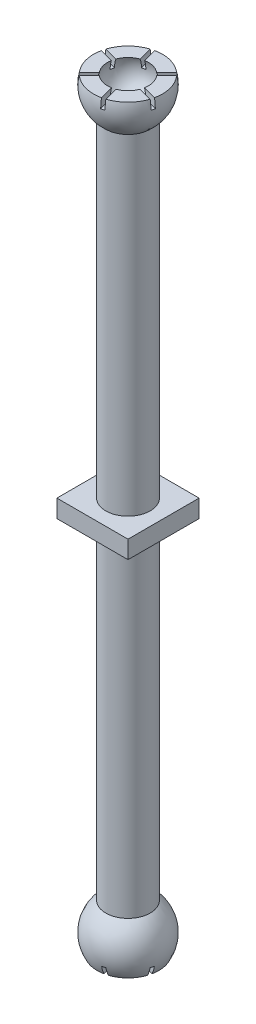
SolidWorks part; units mm, degrees
material "AISI 1020 Steel, Cold Rolled"
ref_plane "Front Plane" through (0, 0, 0) normal (0, 0, 1) x (1, 0, 0)
ref_plane "Top Plane" through (0, 0, 0) normal (0, 1, 0) x (1, 0, 0)
ref_plane "Right Plane" through (0, 0, 0) normal (1, 0, 0) x (0, 0, -1)
sketch "Sketch1" plane through (0, 0, 0) normal (0, 1, 0) x (1, 0, 0)
  circle A0 centre (0, 0) radius 25
  dimension "D1" = 50
extrude "Boss-Extrude1" add sketch "Sketch1" along normal blind 826
ref_plane "Plane1" through (0, 826, 0) normal (0, 1, 0) x (1, 0, 0)
sketch "Sketch2" plane through (0, 826, 0) normal (0, 1, 0) x (1, 0, 0)
  line L0 (0, 40) -> (0, -40)
  arc A0 (0, 40) -> (0, -40) centre (0, 0) ccw
  dimension "D1" = 40
revolve "Revolve1" add sketch "Sketch2" angle 360 about L0
ref_plane "Plane2" through (0, 836, 0) normal (0, 1, 0) x (1, 0, 0)
sketch "Sketch3" plane through (0, 0, 0) normal (0, -1, 0) x (1, 0, 0)
  line L0 (0, 40) -> (0, -40)
  arc A0 (0, 40) -> (0, -40) centre (0, 0) cw
  circle A1 centre (0, 0) radius 40 construction
sketch "Sketch4" plane through (0, 836, 0) normal (0, 1, 0) x (1, 0, 0)
  circle A0 centre (0, 0) radius 43.9337
extrude "Cut-Extrude1" cut sketch "Sketch4" along normal through all
ref_plane "Plane3" through (0, -10, 0) normal (0, -1, 0) x (-1, 0, 0)
revolve "Revolve3" add sketch "Sketch3" angle 360 about L0
ref_plane "Plane4" through (0, -20, 0) normal (0, -1, 0) x (-1, 0, 0)
sketch "Sketch6" plane through (0, -20, 0) normal (0, -1, 0) x (-1, 0, 0)
  circle A0 centre (0, 0) radius 44.2735
extrude "Cut-Extrude2" cut sketch "Sketch6" along normal through all
sketch "Sketch7" plane through (0, 826, 0) normal (0, 1, 0) x (1, 0, 0)
  line L0 (14.2673, 20.5291) -> (-14.2673, -20.5291)
  arc A0 (14.2673, 20.5291) -> (-14.2673, -20.5291) centre (0, 0) ccw
  dimension "D1" = 25
sketch "Sketch8" plane through (0, 826, 0) normal (0, 1, 0) x (1, 0, 0)
  line L7 (1.0353, 3.8637) -> (-9.4733, 43.0824)
  line L9 (-3.8637, -1.0353) -> (-32.5738, -29.7453)
  line L10 (-1.0353, -3.8637) -> (9.4733, -43.0824)
  line L11 (2.8284, -2.8284) -> (42.0471, -13.337)
  line L12 (1.0353, 3.8637) -> (29.7453, 32.5738)
  line L13 (-2.8284, 2.8284) -> (-13.337, 42.0471)
  line L14 (-3.8637, -1.0353) -> (-43.0824, 9.4733)
  line L15 (-1.0353, -3.8637) -> (-29.7453, -32.5738)
  line L16 (2.8284, -2.8284) -> (13.337, -42.0471)
  line L18 (-2.8284, 2.8284) -> (-42.0471, 13.337)
  line L28 (3.8637, 1.0353) -> (43.0824, -9.4733)
  line L30 (3.8637, 1.0353) -> (32.5738, 29.7453)
  arc A0 (-32.5738, -29.7453) -> (-29.7453, -32.5738) centre (0, 0) ccw
  arc A1 (-42.0471, 13.337) -> (-43.0824, 9.4733) centre (0, 0) ccw
  arc A2 (-9.4733, 43.0824) -> (-13.337, 42.0471) centre (0, 0) ccw
  arc A3 (32.5738, 29.7453) -> (29.7453, 32.5738) centre (0, 0) ccw
  arc A4 (42.0471, -13.337) -> (43.0824, -9.4733) centre (0, 0) ccw
  arc A5 (9.4733, -43.0824) -> (13.337, -42.0471) centre (0, 0) ccw
  point P1 (33.8025, 33.8025)
  point P6 (46.1751, -12.3726)
  point P7 (12.3726, -46.1751)
  point P8 (-33.8025, -33.8025)
  point P9 (-46.1751, 12.3726)
  point P10 (-12.3726, 46.1751)
  point P11 (0, 0)
  point P13 (0.5176, 1.9319)
  point P14 (-45.6575, 14.3044)
  point P15 (-1.4142, 1.4142)
  point P16 (-35.2168, -32.3883)
  point P21 (-1.4142, 1.4142)
  point P22 (32.3883, 35.2168)
extrude "Cut-Extrude3" cut sketch "Sketch8" along normal through all
revolve "Cut-Revolve1" cut sketch "Sketch7" angle 360 about L0
sketch "Sketch9" plane through (0, -10, 0) normal (0, -1, 0) x (-1, 0, 0)
  line L0 (17.1936, 18.1488) -> (-17.1936, -18.1488)
  arc A0 (17.1936, 18.1488) -> (-17.1936, -18.1488) centre (0, 0) ccw
  dimension "D1" = 25
revolve "Cut-Revolve2" cut sketch "Sketch9" angle 360 about L0
sketch "Sketch10" plane through (0, -10, 0) normal (0, -1, 0) x (-1, 0, 0)
  line L12 (-1.0353, 3.8637) -> (-29.7453, 32.5738)
  line L13 (-32.5738, 29.7453) -> (-3.8637, 1.0353)
  line L14 (-3.8637, 1.0353) -> (-43.0824, -9.4733)
  line L15 (-42.0471, -13.337) -> (-2.8284, -2.8284)
  line L16 (-2.8284, -2.8284) -> (-13.337, -42.0471)
  line L17 (-9.4733, -43.0824) -> (1.0353, -3.8637)
  line L18 (1.0353, -3.8637) -> (29.7453, -32.5738)
  line L19 (32.5738, -29.7453) -> (3.8637, -1.0353)
  line L20 (3.8637, -1.0353) -> (43.0824, 9.4733)
  line L21 (42.0471, 13.337) -> (2.8284, 2.8284)
  line L22 (2.8284, 2.8284) -> (13.337, 42.0471)
  line L23 (9.4733, 43.0824) -> (-1.0353, 3.8637)
  line L24 (-1.0353, 3.8637) -> (-29.7453, 32.5738)
  line L25 (-32.5738, 29.7453) -> (-3.8637, 1.0353)
  line L26 (-3.8637, 1.0353) -> (-43.0824, -9.4733)
  line L27 (-42.0471, -13.337) -> (-2.8284, -2.8284)
  line L28 (-2.8284, -2.8284) -> (-13.337, -42.0471)
  line L29 (-9.4733, -43.0824) -> (1.0353, -3.8637)
  line L30 (1.0353, -3.8637) -> (29.7453, -32.5738)
  line L31 (32.5738, -29.7453) -> (3.8637, -1.0353)
  line L32 (3.8637, -1.0353) -> (43.0824, 9.4733)
  line L33 (42.0471, 13.337) -> (2.8284, 2.8284)
  line L34 (2.8284, 2.8284) -> (13.337, 42.0471)
  line L35 (9.4733, 43.0824) -> (-1.0353, 3.8637)
  arc A6 (-29.7453, 32.5738) -> (-32.5738, 29.7453) centre (0, 0) ccw
  arc A7 (-43.0824, -9.4733) -> (-42.0471, -13.337) centre (0, 0) ccw
  arc A8 (-13.337, -42.0471) -> (-9.4733, -43.0824) centre (0, 0) ccw
  arc A9 (29.7453, -32.5738) -> (32.5738, -29.7453) centre (0, 0) ccw
  arc A10 (43.0824, 9.4733) -> (42.0471, 13.337) centre (0, 0) ccw
  arc A11 (13.337, 42.0471) -> (9.4733, 43.0824) centre (0, 0) ccw
  arc A12 (-29.7453, 32.5738) -> (-32.5738, 29.7453) centre (0, 0) ccw
  arc A13 (-43.0824, -9.4733) -> (-42.0471, -13.337) centre (0, 0) ccw
  arc A14 (-13.337, -42.0471) -> (-9.4733, -43.0824) centre (0, 0) ccw
  arc A15 (29.7453, -32.5738) -> (32.5738, -29.7453) centre (0, 0) ccw
  arc A16 (43.0824, 9.4733) -> (42.0471, 13.337) centre (0, 0) ccw
  arc A17 (13.337, 42.0471) -> (9.4733, 43.0824) centre (0, 0) ccw
  dimension "D1" = 0
extrude "Cut-Extrude4" cut sketch "Sketch10" along normal through all
ref_plane "Plane5" through (0, 413, 0) normal (0, 1, 0) x (1, 0, 0)
sketch "Sketch11" plane through (0, 413, 0) normal (0, 1, 0) x (1, 0, 0)
  line L1 (-40, 40) -> (40, 40)
  line L2 (-40, 40) -> (-40, -40)
  line L3 (-40, -40) -> (40, -40)
  line L4 (40, 40) -> (40, -40)
  line L5 (-40, 40) -> (40, -40) construction
  line L6 (-40, -40) -> (40, 40) construction
  point P0 (0, 0)
  dimension "D1" = 80
  dimension "D2" = 80
extrude "Boss-Extrude2" add sketch "Sketch11" along normal mid plane 20
